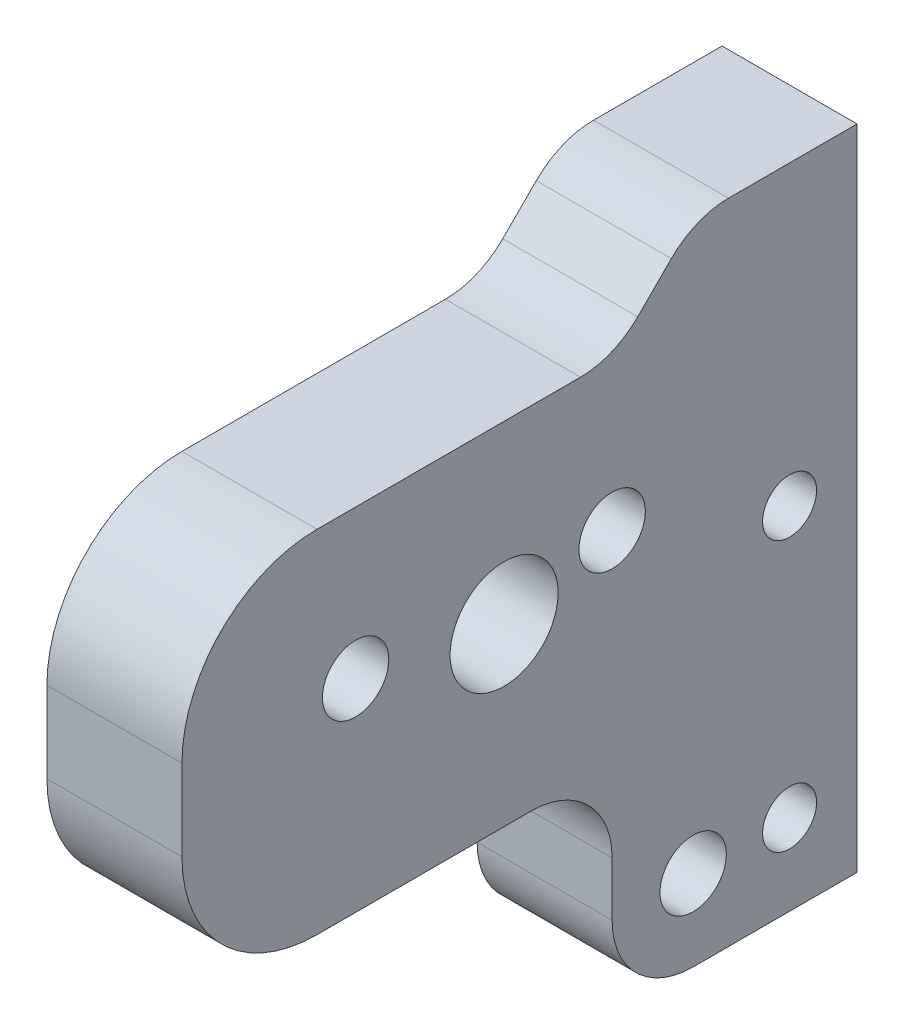
SolidWorks part; units mm, degrees
ref_plane "Front Plane" through (0, 0, 0) normal (1, 0, 0) x (0, 1, 0)
ref_plane "Top Plane" through (0, 0, 0) normal (0, 0, 1) x (0, 1, 0)
ref_plane "Right Plane" through (0, 0, 0) normal (0, 1, 0) x (-1, 0, 0)
sketch "Sketch1" plane through (0, 0, 0) normal (1, 0, 0) x (0, 1, 0)
  line L0 (-11.7291, -13.4323) -> (-11.7291, -7.3623)
  line L1 (-8.7291, -4.3623) -> (-6.7291, -4.3623)
  line L2 (-3.7291, -1.3623) -> (-3.7291, 11.5677)
  line L4 (9.2709, 8.5677) -> (9.2709, -3.1896)
  line L5 (11.3922, -6.5536) -> (10.1495, -5.311)
  line L6 (12.2709, -8.6749) -> (12.2709, -13.4323)
  line L7 (12.2709, -13.4323) -> (-11.7291, -13.4323)
  line L8 (3.7709, -4.3623) -> (3.7709, 5.1377) construction
  line L9 (3.7709, 0.3877) -> (-3.7291, 0.3877) construction
  line L10 (-3.7291, 11.5677) -> (9.2709, 11.5677)
  line L11 (9.2709, 11.5677) -> (9.2709, 8.5677)
  arc A0 (-8.7291, -4.3623) -> (-11.7291, -7.3623) centre (-8.7291, -7.3623) ccw
  arc A1 (-6.7291, -4.3623) -> (-3.7291, -1.3623) centre (-6.7291, -1.3623) ccw
  arc A4 (9.2709, -3.1896) -> (10.1495, -5.311) centre (12.2709, -3.1896) ccw
  arc A5 (12.2709, -8.6749) -> (11.3922, -6.5536) centre (9.2709, -8.6749) ccw
  circle A6 centre (3.7709, 5.1377) radius 1.2295
  circle A7 centre (2.7709, -0.3623) radius 2
  circle A8 centre (3.7709, -4.3623) radius 1.2295
  circle A9 centre (-8.7291, -7.3623) radius 1.2295
  circle A10 centre (-8.7291, -10.9323) radius 1
  circle A11 centre (1.2709, -10.9323) radius 1
  dimension "D1" = 7.5
  dimension "D2" = 9.5
  dimension "D3" = 90
  dimension "D4" = 13.07
  dimension "D5" = 13.82
extrude "Boss-Extrude1" add sketch "Sketch1" along normal blind 5
sketch "Sketch2" plane through (0, 0, -13.4323) normal (0, 0, -1) x (1, 0, 0)
  line L0 (5, -12.2709) -> (0, -12.2709) construction
  line L1 (5, 11.7291) -> (5, -12.2709) construction
  circle A0 centre (2.5, -8.7709) radius 1.25
  circle A1 centre (2.5, 5.2291) radius 1.25
  dimension "D1" = 2.5
  dimension "D2" = 2.5
  dimension "D4" = 14
  dimension "D5" = 2.5
  dimension "D6" = 2.5
  dimension "D3" = 3.5
extrude "Cut-Extrude1" cut sketch "Sketch2" against normal blind 5
sketch "Sketch8" plane through (0, 0, -13.4323) normal (0, 0, -1) x (1, 0, 0)
  line L0 (5, 11.7291) -> (5, -12.2709) construction
  line L1 (5, -12.2709) -> (0, -12.2709) construction
  circle A0 centre (2.5, -8.7709) radius 1.5
  circle A1 centre (2.5, 5.2291) radius 1.5
  dimension "D1" = 3
  dimension "D2" = 3
  dimension "D4" = 2.5
  dimension "D5" = 2.5
  dimension "D6" = 3.5
  dimension "D3" = 14
fillet "Fillet1" radius 5 2 edges at (2.5, 9.2709, 11.5677) (2.5, -3.7291, 11.5677)
